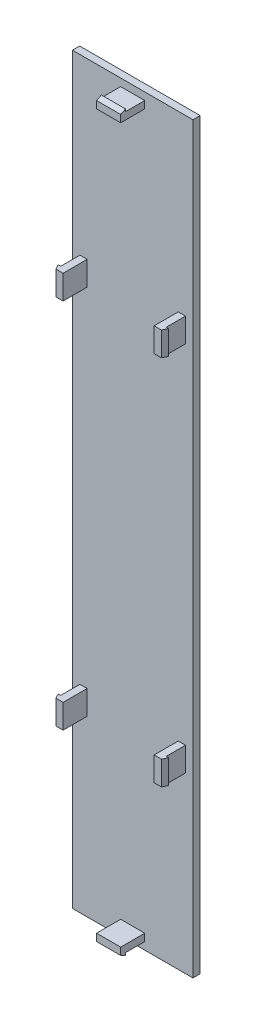
SolidWorks part; units mm, degrees
ref_plane "Front Plane" through (0, 0, 0) normal (1, 0, 0) x (0, 1, 0)
ref_plane "Top Plane" through (0, 0, 0) normal (0, 0, 1) x (0, 1, 0)
ref_plane "Right Plane" through (0, 0, 0) normal (0, 1, 0) x (-1, 0, 0)
sketch "Sketch2" plane through (0, 0, 0) normal (0, 0, 1) x (0, 1, 0)
  line L1 (0, 0) -> (154.25, 0)
  line L2 (0, 0) -> (0, 25)
  line L3 (0, 25) -> (154.25, 25)
  line L4 (154.25, 0) -> (154.25, 25)
  dimension "D1" = 154.25
  dimension "D2" = 25
extrude "Boss-Extrude1" add sketch "Sketch2" along normal blind 1.5
sketch "Sketch3" plane through (0, 0, 1.5) normal (0, 0, 1) x (1, 0, 0)
  line L1 (-12.5, 0) -> (-12.5, 12.7961) construction
  line L2 (-25, 0) -> (0, 0) construction
  line L4 (-15, 1.55) -> (-10, 1.55)
  line L5 (-15, 1.55) -> (-15, 3.05)
  line L6 (-15, 3.05) -> (-10, 3.05)
  line L7 (-10, 1.55) -> (-10, 3.05)
  line L8 (-15, 1.55) -> (-10, 3.05) construction
  line L9 (-15, 3.05) -> (-10, 1.55) construction
  point P5 (-12.5, 2.3)
  dimension "D1" = 5
  dimension "D2" = 1.5
  dimension "D3" = 1.55
extrude "Boss-Extrude2" add sketch "Sketch3" along normal blind 5
sketch "Sketch4" plane through (-10, 0, 0) normal (1, 0, 0) x (0, 1, 0)
  line L0 (1.55, 6.5) -> (1.05, 5.5)
  line L1 (1.05, 5.5) -> (1.55, 5.5)
  line L3 (1.55, 5.5) -> (1.55, 6.5)
  line L4 (1.55, 6.5) -> (1.55, 1.5) construction
  dimension "D2" = 1
extrude "Boss-Extrude3" add sketch "Sketch4" against normal blind 5
sketch "Sketch5" plane through (0, 0, 1.5) normal (0, 0, 1) x (1, 0, 0)
  line L0 (0, 77.125) -> (-56.7315, 77.125) construction
  line L1 (0, 0) -> (0, 154.25) construction
  line L2 (0, 77.125) -> (0, 0) construction
  line L3 (0, 77.125) -> (0, 154.25) construction
  line L4 (-3.05, 113.1875) -> (-1.55, 118.1875) construction
  line L5 (0, 38.5625) -> (-27.5743, 38.5625) construction
  line L6 (-3.05, 118.1875) -> (-1.55, 113.1875) construction
  line L7 (-3.05, 36.0625) -> (-1.55, 36.0625)
  line L8 (-3.05, 36.0625) -> (-3.05, 41.0625)
  line L9 (-3.05, 41.0625) -> (-1.55, 41.0625)
  line L10 (-1.55, 36.0625) -> (-1.55, 41.0625)
  line L11 (-3.05, 36.0625) -> (-1.55, 41.0625) construction
  line L12 (-3.05, 41.0625) -> (-1.55, 36.0625) construction
  line L13 (0, 115.6875) -> (-27.5743, 115.6875) construction
  line L14 (0, 77.125) -> (0, 154.25) construction
  line L15 (-1.55, 118.1875) -> (-1.55, 113.1875)
  line L16 (-3.05, 113.1875) -> (-1.55, 113.1875)
  line L17 (-3.05, 118.1875) -> (-3.05, 113.1875)
  line L18 (-3.05, 118.1875) -> (-1.55, 118.1875)
  point P4 (0, 38.5625)
  point P14 (-2.3, 38.5625)
  point P22 (-2.3, 115.6875)
  point P23 (0, 115.6875)
  dimension "D3" = 1.55
  dimension "D1" = 1.5
  dimension "D2" = 5
extrude "Boss-Extrude4" add sketch "Sketch5" along normal blind 5
sketch "Sketch6" plane through (0, 36.0625, 0) normal (0, -1, 0) x (1, 0, 0)
  line L0 (-1.55, 6.5) -> (-1.05, 5.5)
  line L1 (-1.05, 5.5) -> (-1.55, 5.5)
  line L3 (-1.55, 5.5) -> (-1.55, 6.5)
  line L4 (-1.55, 6.5) -> (-1.55, 1.5) construction
  dimension "D2" = 1
extrude "Boss-Extrude5" add sketch "Sketch6" against normal blind 5 contours L0 L1 L3
ref_plane "Plane1" through (0, 77.125, 0) normal (0, -1, 0) x (-1, 0, 0)
mirror "Mirror2" about plane through (0, 77.125, 0) normal (0, -1, 0) of "Boss-Extrude5"
mirror "Mirror3" about plane through (0, 77.125, 0) normal (0, -1, 0) of "Boss-Extrude2"
mirror "Mirror4" about plane through (0, 77.125, 0) normal (0, -1, 0) of "Boss-Extrude3"
ref_plane "Plane2" through (-12.5, 0, 0) normal (1, 0, 0) x (0, 0, -1)
mirror "Mirror5" about plane through (-12.5, 0, 0) normal (1, 0, 0) of "Mirror2", "Boss-Extrude4", "Boss-Extrude5"
equation "\"SSD1306_screen_w\" = 11.5mm"
equation "\"SSD1306_screen_l\" = 30mm"
equation "\"SSD1306_screen_t\" = 1.5mm"
equation "\"SSD1306_screen_marge\" = 0.25mm"
equation "\"SSD1306_PCB_Screen_H\" = 7.3mm"
equation "\"clip_h\" = 5mm"
equation "\"clip_l\" = 5mm"
equation "\"clip_w\" = 1.5mm"
equation "\"clip_lip_h\" = 1mm"
equation "\"clip_lip_l\" = 0.5mm"
equation "\"D1@Sketch4\"=\"clip_lip_l\""
equation "\"D2@Sketch4\"=\"clip_lip_h\""
equation "\"D1@Sketch3\"=\"clip_l\""
equation "\"D2@Sketch3\"=\"clip_w\""
equation "\"D1@Boss-Extrude2\"=\"clip_h\""
equation "\"D1@Sketch5\"=\"clip_w\""
equation "\"D2@Sketch5\"=\"clip_l\""
equation "\"D1@Boss-Extrude4\"=\"clip_h\""
equation "\"D1@Sketch6\"=\"clip_lip_l\""
equation "\"D2@Sketch6\"=\"clip_lip_h\""
equation "\"D1@Boss-Extrude5\"=\"clip_l\""
equation "\"D1@Boss-Extrude3\"=\"clip_l\""
